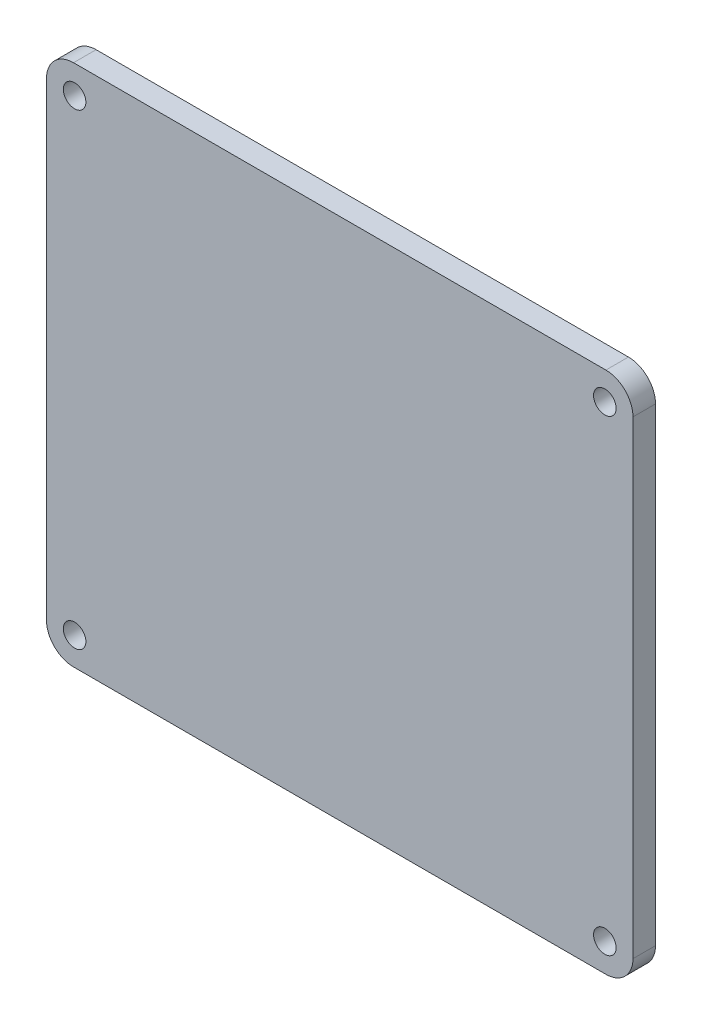
SolidWorks part; units mm, degrees
ref_plane "Front Plane" through (0, 0, 0) normal (0, 0, 1) x (1, 0, 0)
ref_plane "Top Plane" through (0, 0, 0) normal (0, 1, 0) x (1, 0, 0)
ref_plane "Right Plane" through (0, 0, 0) normal (1, 0, 0) x (0, 0, -1)
sketch "Base Sketch" plane through (0, 0, 0) normal (0, 0, 1) x (1, 0, 0)
  line L1 (0, 0) -> (65, 0)
  line L2 (0, 0) -> (0, 58)
  line L3 (0, 58) -> (65, 58)
  line L4 (65, 0) -> (65, 58)
  line L5 (5, 53) -> (60, 53)
  line L6 (5, 53) -> (5, 5)
  line L7 (5, 5) -> (60, 5)
  line L8 (60, 53) -> (60, 5)
  line L9 (5, 48) -> (7, 48)
  line L10 (5, 48) -> (5, 45)
  line L11 (5, 45) -> (7, 45)
  line L12 (7, 48) -> (7, 45)
  line L17 (44, 5) -> (47, 5)
  line L18 (44, 5) -> (44, 7)
  line L19 (44, 7) -> (47, 7)
  line L20 (47, 5) -> (47, 7)
  line L21 (60, 30) -> (58, 30)
  line L22 (60, 30) -> (60, 33)
  line L23 (60, 33) -> (58, 33)
  line L24 (58, 30) -> (58, 33)
  point P9 (32.5, 58)
  point P10 (32.5, 53)
  point P11 (0, 29)
  point P12 (5, 29)
  point P25 (47, 6)
  point P26 (6, 45)
  point P27 (59, 33)
  point P28 (6, 48)
  point P29 (44, 6)
  dimension "D1" = 65
  dimension "D2" = 55
  dimension "D3" = 58
  dimension "D4" = 48
  dimension "D5" = 5
  dimension "D6" = 3
  dimension "D7" = 2
  dimension "D8" = 3
  dimension "D9" = 3
  dimension "D10" = 2
  dimension "D11" = 13
  dimension "D12" = 2
  dimension "D13" = 20
  dimension "D14" = 53
  dimension "D15" = 42
sketch "Mounting Holes" plane through (0, 0, 0) normal (0, 0, 1) x (1, 0, 0)
  line L0 (5, 53) -> (0, 58) construction
  line L1 (60, 53) -> (65, 58) construction
  line L2 (60, 5) -> (65, 0) construction
  line L3 (0, 0) -> (5, 5) construction
  line L4 (3.1155, 54.8845) -> (65, 54.8845) construction
  line L6 (61.8845, 54.8845) -> (61.8845, 0) construction
  line L8 (61.8845, 3.1155) -> (0, 3.1155) construction
  circle A0 centre (3.1155, 54.8845) radius 1.25
  circle A1 centre (61.8845, 54.8845) radius 1.25
  circle A2 centre (61.8845, 3.1155) radius 1.25
  circle A3 centre (3.1155, 3.1155) radius 1.25
  point P12 (0, 0)
  point P25 (3.1155, 3.1155)
  point P29 (3.1155, 3.1155)
  point P33 (2.5, 55.5)
  dimension "D1" = 2.5
  dimension "D2" = 2.5
  dimension "D3" = 2.5
  dimension "D4" = 2.5
extrude "Boss-Extrude2" add sketch "Base Sketch" along normal blind 2.5 contours L2 L3 L4 L1
extrude "Cut-Extrude5" cut sketch "Mounting Holes" along normal blind 2.5
fillet "Fillet1" radius 3 4 edges at (65, 58, 1.25) (65, 0, 1.25) (0, 0, 1.25) (0, 58, 1.25)
